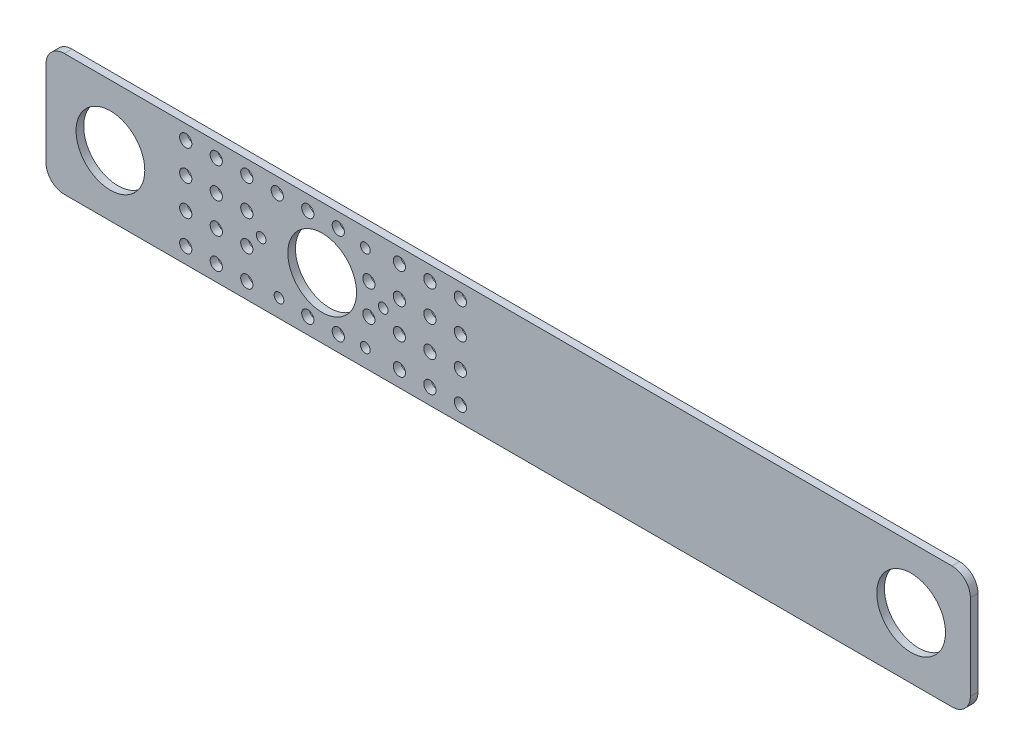
SolidWorks part; units mm, degrees
ref_plane "Front Plane" through (0, 0, 0) normal (0, 0, 1) x (1, 0, 0)
ref_plane "Top Plane" through (0, 0, 0) normal (0, 1, 0) x (1, 0, 0)
ref_plane "Right Plane" through (0, 0, 0) normal (1, 0, 0) x (0, 0, -1)
sketch "Sketch1" plane through (0, 0, 0) normal (0, 0, 1) x (1, 0, 0)
  line L1 (-100.9194, 26.073) -> (283.7947, 26.073)
  line L2 (-100.9194, 26.073) -> (-100.9194, -24.727)
  line L3 (-100.9194, -24.727) -> (283.7947, -24.727)
  line L4 (283.7947, 26.073) -> (283.7947, -24.727)
  circle A0 centre (-74.1099, 0.673) radius 14.3002
  circle A1 centre (14.0281, 0.673) radius 14.3002
  circle A2 centre (259.1381, 0.673) radius 14.3002
  circle A4 centre (39.4224, 0.663) radius 2.0193
  circle A5 centre (31.9829, -17.2976) radius 2.0193
  circle A6 centre (-3.9381, -17.2976) radius 2.0193
  circle A7 centre (31.9829, 18.6235) radius 2.0193
  circle A8 centre (-11.3776, 0.663) radius 2.0193
  circle A9 centre (-30.0553, 7.2896) radius 2.54 construction
  circle A10 centre (-30.0553, -5.4104) radius 2.54 construction
  circle A11 centre (-17.3553, 7.2896) radius 2.54 construction
  circle A12 centre (-17.3553, -5.4104) radius 2.54 construction
  circle A13 centre (-17.3553, -18.1104) radius 2.54 construction
  circle A14 centre (-17.3553, 19.9896) radius 2.54 construction
  circle A15 centre (-30.0668, 19.9896) radius 2.54 construction
  circle A16 centre (33.4447, -5.4104) radius 2.54 construction
  circle A17 centre (33.4447, 7.2896) radius 2.54 construction
  circle A18 centre (58.8447, -5.4104) radius 2.54 construction
  circle A19 centre (58.8447, 7.2896) radius 2.54 construction
  circle A20 centre (46.1447, 7.2896) radius 2.54 construction
  circle A21 centre (46.1447, -5.4104) radius 2.54 construction
  circle A22 centre (46.1447, -18.1104) radius 2.54 construction
  circle A23 centre (58.8332, -18.1104) radius 2.54 construction
  circle A24 centre (71.5332, -18.1104) radius 2.54 construction
  circle A25 centre (71.5332, -5.4104) radius 2.54 construction
  circle A26 centre (71.5332, 7.2896) radius 2.54 construction
  circle A27 centre (71.5332, 19.9896) radius 2.54 construction
  circle A28 centre (58.8332, 19.9896) radius 2.54 construction
  circle A29 centre (46.1447, 19.9896) radius 2.54 construction
  circle A30 centre (20.7332, 19.9896) radius 2.54 construction
  circle A31 centre (8.0332, 19.9896) radius 2.54 construction
  circle A32 centre (-4.6668, 19.9896) radius 2.54 construction
  circle A33 centre (20.7332, -18.1104) radius 2.54 construction
  circle A34 centre (8.0332, -18.1104) radius 2.54 construction
  circle A35 centre (-30.0668, -18.1104) radius 2.54 construction
  circle A36 centre (-42.7668, -18.1104) radius 2.54 construction
  circle A37 centre (-42.7668, 19.9896) radius 2.54 construction
  circle A38 centre (-42.7668, 7.2896) radius 2.54 construction
  circle A39 centre (-42.7668, -5.4104) radius 2.54 construction
  circle A40 centre (-30.0553, 7.2896) radius 2.54
  circle A41 centre (-30.0553, -5.4104) radius 2.54
  circle A42 centre (-17.3553, 7.2896) radius 2.54
  circle A43 centre (-17.3553, -5.4104) radius 2.54
  circle A44 centre (-17.3553, -18.1104) radius 2.54
  circle A45 centre (-17.3553, 19.9896) radius 2.54
  circle A46 centre (-30.0668, 19.9896) radius 2.54
  circle A47 centre (33.4447, -5.4104) radius 2.54
  circle A48 centre (33.4447, 7.2896) radius 2.54
  circle A49 centre (58.8447, -5.4104) radius 2.54
  circle A50 centre (58.8447, 7.2896) radius 2.54
  circle A51 centre (46.1447, 7.2896) radius 2.54
  circle A52 centre (46.1447, -5.4104) radius 2.54
  circle A53 centre (46.1447, -18.1104) radius 2.54
  circle A54 centre (58.8332, -18.1104) radius 2.54
  circle A55 centre (71.5332, -18.1104) radius 2.54
  circle A56 centre (71.5332, -5.4104) radius 2.54
  circle A57 centre (71.5332, 7.2896) radius 2.54
  circle A58 centre (71.5332, 19.9896) radius 2.54
  circle A59 centre (58.8332, 19.9896) radius 2.54
  circle A60 centre (46.1447, 19.9896) radius 2.54
  circle A61 centre (20.7332, 19.9896) radius 2.54
  circle A62 centre (8.0332, 19.9896) radius 2.54
  circle A63 centre (-4.6668, 19.9896) radius 2.54
  circle A64 centre (20.7332, -18.1104) radius 2.54
  circle A65 centre (8.0332, -18.1104) radius 2.54
  circle A66 centre (-30.0668, -18.1104) radius 2.54
  circle A67 centre (-42.7668, -18.1104) radius 2.54
  circle A68 centre (-42.7668, 19.9896) radius 2.54
  circle A69 centre (-42.7668, 7.2896) radius 2.54
  circle A70 centre (-42.7668, -5.4104) radius 2.54
  dimension "D3" = 88.138
  dimension "D1" = 50.8
  dimension "D2" = 25.4
  dimension "D4" = 245.11
  dimension "D5" = 25.4
  dimension "D6" = 25.4
extrude "Boss-Extrude1" add sketch "Sketch1" along normal blind 3.175
fillet "Fillet1" radius 7.62 4 edges at (283.7947, -24.727, 1.5875) (283.7947, 26.073, 1.5875) (-100.9194, -24.727, 1.5875) (-100.9194, 26.073, 1.5875)
